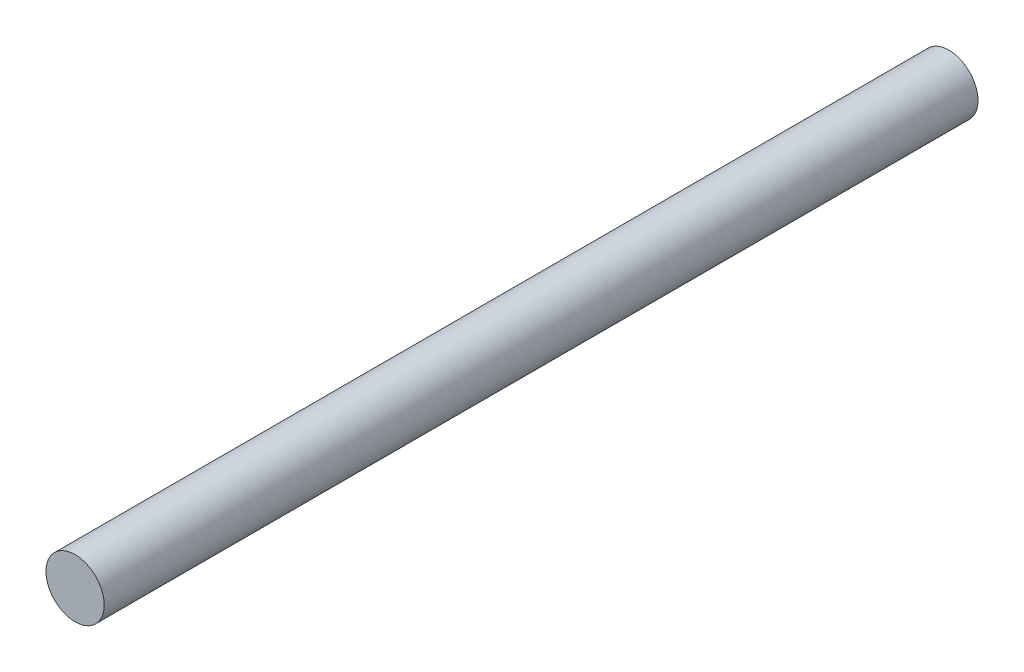
SolidWorks part; units mm, degrees
ref_plane "Спереди" through (0, 0, 0) normal (0, 0, 1) x (1, 0, 0)
ref_plane "Сверху" through (0, 0, 0) normal (0, 1, 0) x (1, 0, 0)
ref_plane "Справа" through (0, 0, 0) normal (1, 0, 0) x (0, 0, -1)
sketch "Эскиз1" plane through (0, 0, 0) normal (0, 0, 1) x (1, 0, 0)
  circle A0 centre (0, 0) radius 2.5
extrude "Вытянуть1" add sketch "Эскиз1" along normal blind 75
